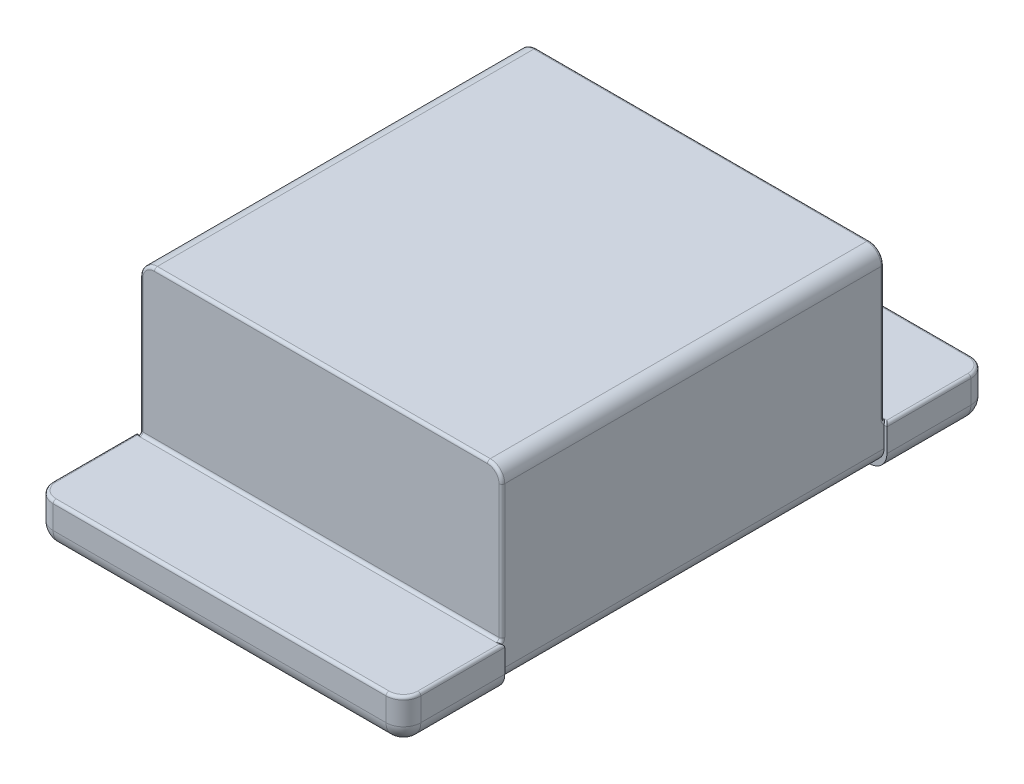
SolidWorks part; units mm, degrees
ref_plane "Front" through (0, 0, 0) normal (0, 0, 1) x (1, 0, 0)
ref_plane "Top" through (0, 0, 0) normal (0, 1, 0) x (1, 0, 0)
ref_plane "Right" through (0, 0, 0) normal (1, 0, 0) x (0, 0, -1)
sketch "Sketch1" plane through (0, 0, 0) normal (0, 1, 0) x (1, 0, 0)
  line L1 (-0.625, 1) -> (0.625, 1)
  line L2 (-0.625, 1) -> (-0.625, -1)
  line L3 (-0.625, -1) -> (0.625, -1)
  line L4 (0.625, 1) -> (0.625, -1)
  line L5 (-0.625, 1) -> (0.625, -1) construction
  line L6 (-0.625, -1) -> (0.625, 1) construction
  point P0 (0, 0)
  dimension "D1" = 2
  dimension "D2" = 1.25
extrude "Boss-Extrude1" add sketch "Sketch1" along normal blind 0.65
fillet "Fillet1" radius 0.05 12 edges at (0.625, 0.325, -1) (-0.625, 0.325, -1) (-0.625, 0.325, 1) (0.625, 0.325, 1) (0, 0, -1) (-0.625, 0, 0) (0, 0, 1) (0.625, 0, 0) (0, 0.65, 1) (-0.625, 0.65, 0) (0, 0.65, -1) (0.625, 0.65, 0)
sketch "Sketch2" plane through (0, 0, 0) normal (0, 1, 0) x (1, 0, 0)
  line L0 (-0.625, -0.95) -> (-0.625, 0.95) construction
  line L1 (-0.635, 1.01) -> (0.635, 1.01)
  line L2 (-0.635, 1.01) -> (-0.635, 0.66)
  line L3 (-0.635, 0.66) -> (0.635, 0.66)
  line L4 (0.635, 1.01) -> (0.635, 0.66)
  line L5 (-0.575, 1) -> (0.575, 1) construction
  point P6 (0, 0.66)
  dimension "D1" = 0.01
  dimension "D2" = 0.01
  dimension "D3" = 0.35
extrude "Boss-Extrude2" add sketch "Sketch2" along normal offset from surface (0.69 mm away) 0.02 from offset 0.02 separate body
fillet "Fillet2" radius 0.06 8 edges at (-0.635, 0.325, -1.01) (0, -0.02, -1.01) (0.635, 0.325, -1.01) (0, 0.67, -1.01) (0.635, -0.02, -0.835) (-0.635, -0.02, -0.835) (-0.635, 0.67, -0.835) (0.635, 0.67, -0.835)
mirror "Mirror1" about plane through (0, 0, 0) normal (0, 0, 1) of bodies 102
sketch "Sketch3" plane through (0, 0, 0) normal (0, 1, 0) x (1, 0, 0)
  line L0 (-0.575, 0.95) -> (-0.575, 0)
  line L1 (-0.575, 0.95) -> (-0.575, -0.95) construction
  line L2 (-0.575, 0) -> (-0.2814, 0.2936)
  line L3 (-0.2814, 0.2936) -> (0.2814, 0.2936)
  line L4 (0.2814, 0.2936) -> (0.575, 0)
  line L5 (0.575, -0.95) -> (0.575, 0.95) construction
  line L6 (0.575, 0) -> (0.575, 0.95)
  line L7 (0.575, 0.95) -> (-0.575, 0.95)
  line L23 (-0.2587, -0.0304) -> (-0.575, -0.1631)
  line L24 (-0.575, -0.1631) -> (-0.575, -0.4188)
  line L25 (-0.575, -0.4188) -> (0.475, -0.4188)
  line L26 (0.475, -0.4188) -> (0.475, -0.5188)
  line L27 (0.475, -0.5188) -> (-0.575, -0.5188)
  line L28 (-0.575, -0.5188) -> (-0.575, -0.95)
  line L29 (-0.575, -0.95) -> (0.575, -0.95)
  line L30 (0.575, -0.95) -> (0.575, -0.3188)
  line L31 (0.575, -0.3188) -> (-0.475, -0.3188)
  line L32 (-0.475, -0.3188) -> (-0.475, -0.2296)
  line L33 (-0.475, -0.2296) -> (-0.2279, -0.126)
  line L34 (-0.3273, -0.0592) -> (-0.2886, -0.1514) construction
  line L35 (-0.575, -0.3188) -> (-0.475, -0.3188) construction
  line L36 (-0.475, -0.3188) -> (-0.475, -0.4188) construction
  line L37 (0.475, -0.4188) -> (0.575, -0.4188) construction
  arc A0 (-0.2279, -0.126) -> (-0.2587, -0.0304) centre (0, 0) ccw
  dimension "D1" = 45
  dimension "D2" = 0.1
extrude "Boss-Extrude3" add sketch "Sketch3" along normal blind 0.1 separate body
sketch "Sketch4" plane through (0, 0, 0) normal (1, 0, 0) x (0, 0, -1)
  line L0 (-1.11, 0.13) -> (-0.66, 0.13)
  line L1 (-0.66, 0.77) -> (0.66, 0.77)
  line L2 (-1.11, 0.13) -> (-1.11, -0.12)
  line L3 (-1.11, -0.12) -> (1.11, -0.12)
  line L4 (1.11, 0.13) -> (1.11, -0.12)
  line L5 (-0.66, 0.13) -> (-0.66, 0.77)
  line L6 (0.66, 0.77) -> (0.66, 0.13)
  line L7 (0.66, 0.13) -> (1.11, 0.13)
  line L8 (-1.01, 0.61) -> (-1.01, 0.04) construction
  line L9 (-0.66, 0.67) -> (-0.95, 0.67) construction
  line L11 (-0.66, 0.61) -> (-0.66, 0.04) construction
  line L12 (-0.95, -0.02) -> (-0.66, -0.02) construction
  point P12 (0, -0.12)
  dimension "D1" = 0.1
  dimension "D2" = 0.1
  dimension "D3" = 0.1
  dimension "D4" = 0.15
extrude "Cut-Extrude1" cut sketch "Sketch4" against normal through all both and the other way through all flip side to cut
fillet "Fillet4" radius 0.01 22 edges at (0, 0.13, -1) (0, 0.13, 1) (-0.6104, 0.13, -0.9854) (0.6104, 0.13, -0.9854) (0.6104, 0.13, 0.9854) (-0.6104, 0.13, 0.9854) (-0.625, 0.13, -0.805) (0.625, 0.13, -0.805) (0.625, 0.13, 0.805) (-0.625, 0.13, 0.805) (0, 0.13, -0.66) (0.625, 0.365, -0.66) (0.6104, 0.6354, -0.66) (0, 0.65, -0.66) (-0.6104, 0.6354, -0.66) (-0.625, 0.365, -0.66) (-0.6104, 0.6354, 0.66) (0, 0.65, 0.66) (0.6104, 0.6354, 0.66) (0.625, 0.365, 0.66) (0, 0.13, 0.66) (-0.625, 0.365, 0.66)
sketch "Sketch5" plane through (0, 0, 0) normal (0, 1, 0) x (1, 0, 0)
  line L0 (0.575, 1.01) -> (-0.575, 1.01) construction
  line L5 (-0.735, 0.67) -> (0.735, 0.67)
  line L6 (-0.735, 0.67) -> (-0.735, 1.11)
  line L7 (-0.735, 1.11) -> (0.735, 1.11)
  line L8 (0.735, 0.67) -> (0.735, 1.11)
  line L9 (-0.615, 0.67) -> (0.615, 0.67) construction
  line L10 (0, 0) -> (-1.6029, 0) construction
  line L11 (-0.735, -0.67) -> (-0.735, -1.11)
  line L12 (-0.735, -0.67) -> (0.735, -0.67)
  line L13 (0.735, -0.67) -> (0.735, -1.11)
  line L14 (-0.735, -1.11) -> (0.735, -1.11)
  line L15 (-0.635, 0.95) -> (-0.635, 0.66) construction
  point P15 (0, 1.11)
  dimension "D1" = 0.1
  dimension "D2" = 0.1
extrude "Cut-Extrude2" cut sketch "Sketch5" along normal through all both and the other way through all
fillet "Fillet5" radius 0.01 6 edges at (0.6174, 0.13, 0.9924) (0, 0.13, 1.01) (-0.6174, 0.13, 0.9924) (-0.635, 0.13, 0.805) (0, 0.13, 0.66) (0.635, 0.13, 0.805)
fillet "Fillet6" radius 0.01 6 edges at (0.6174, 0.13, -0.9924) (0.635, 0.13, -0.805) (0, 0.13, -0.66) (-0.635, 0.13, -0.805) (-0.6174, 0.13, -0.9924) (0, 0.13, -1.01)
equation "\"D2@Sketch2\"=\"D1@Sketch2\""
equation "\"D2@Sketch4\"=\"D1@Sketch4\""
equation "\"D3@Sketch4\"=\"D1@Sketch4\""
equation "\"D2@Sketch5\"=\"D1@Sketch5\""
